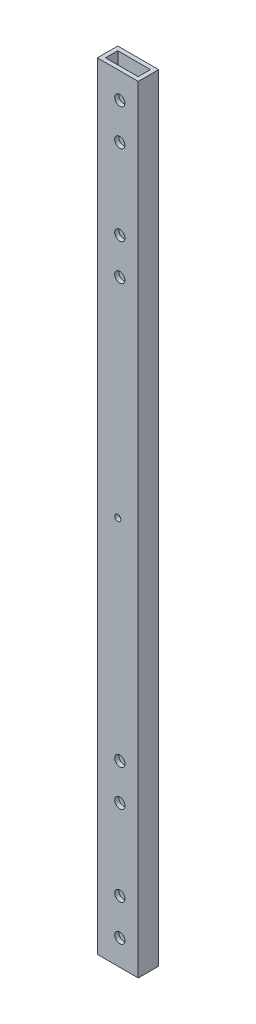
SolidWorks part; units mm, degrees
material "6061 合金"
ref_plane "前视基准面" through (0, 0, 0) normal (0, 0, 1) x (1, 0, 0)
ref_plane "上视基准面" through (0, 0, 0) normal (0, 1, 0) x (1, 0, 0)
ref_plane "右视基准面" through (0, 0, 0) normal (1, 0, 0) x (0, 0, -1)
sketch "草图1" plane through (0, 0, 0) normal (0, 1, 0) x (1, 0, 0)
  line L0 (8, 3) -> (-8, 3)
  line L1 (10, -5) -> (-10, -5)
  line L2 (10, -5) -> (10, 5)
  line L3 (10, 5) -> (-10, 5)
  line L4 (-10, -5) -> (-10, 5)
  line L5 (10, -5) -> (-10, 5) construction
  line L6 (10, 5) -> (-10, -5) construction
  line L7 (-8, -3) -> (-8, 3)
  line L8 (8, -3) -> (-8, -3)
  line L9 (8, -3) -> (8, 3)
  point P0 (0, 0)
  dimension "D1" = 20
  dimension "D2" = 10
  dimension "D3" = 2
extrude "凸台-拉伸1" add sketch "草图1" along normal mid plane 380
sketch "草图2" plane through (0, 0, 5) normal (0, 0, 1) x (1, 0, 0)
  line L0 (-10, -190) -> (10, -190) construction
  line L1 (10, 190) -> (10, -190) construction
  line L2 (-10, 0) -> (10, 0) construction
  line L3 (-10, 190) -> (-10, -190) construction
  circle A0 centre (1, -177.5) radius 2.5
  circle A1 centre (1, -159.7) radius 2.5
  circle A2 centre (1, -120.3) radius 2.5
  circle A3 centre (1, -102.5) radius 2.5
  circle A4 centre (1, 102.5) radius 2.5
  circle A5 centre (1, 120.3) radius 2.5
  circle A6 centre (1, 159.7) radius 2.5
  circle A7 centre (1, 177.5) radius 2.5
  dimension "D1" = 5
  dimension "D2" = 5
  dimension "D3" = 12.5
  dimension "D4" = 9
  dimension "D5" = 17.8
  dimension "D6" = 5
  dimension "D7" = 5
  dimension "D8" = 39.4
  dimension "D9" = 17.8
extrude "切除-拉伸1" cut sketch "草图2" against normal through all
sketch "草图3" plane through (0, 0, -5) normal (0, 0, -1) x (-1, 0, 0)
  circle A0 centre (0, 0) radius 1.5
  dimension "D1" = 3
extrude "切除-拉伸2" cut sketch "草图3" against normal through all
